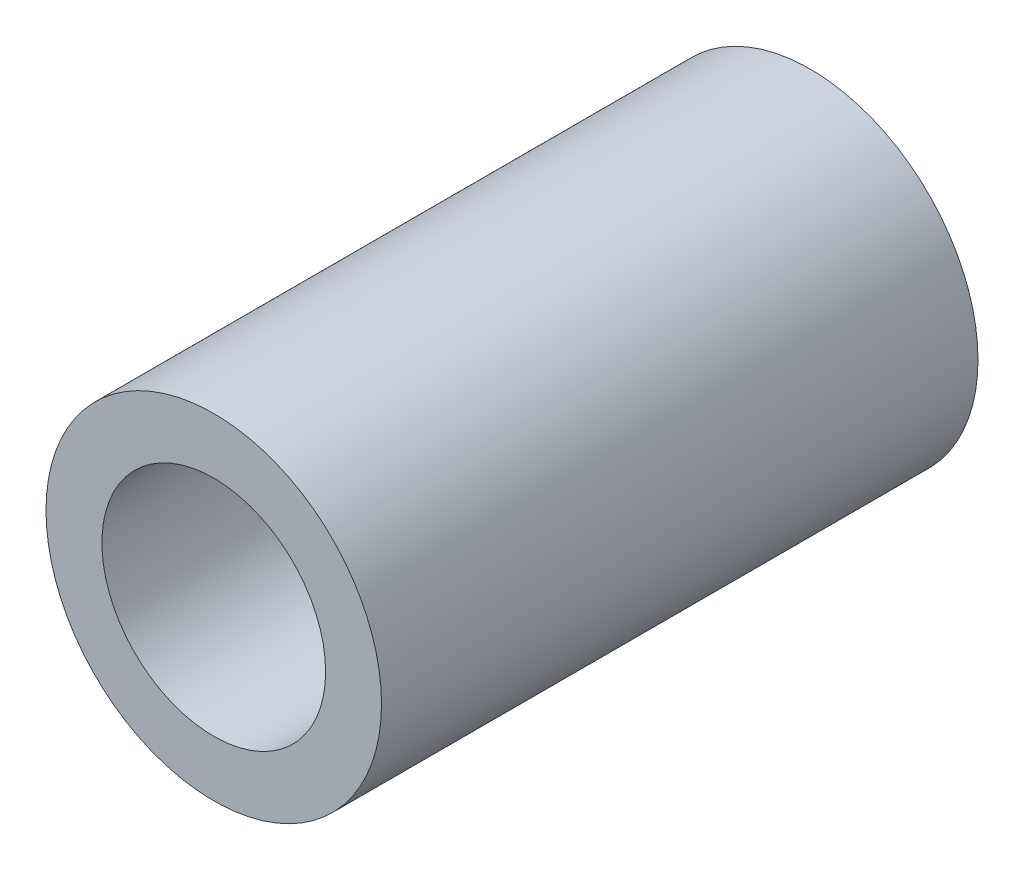
SolidWorks part; units mm, degrees
ref_plane "Płaszczyzna przednia" through (0, 0, 0) normal (0, 0, 1) x (1, 0, 0)
ref_plane "Płaszczyzna górna" through (0, 0, 0) normal (0, 1, 0) x (1, 0, 0)
ref_plane "Płaszczyzna prawa" through (0, 0, 0) normal (1, 0, 0) x (0, 0, -1)
sketch "Sketch1" plane through (0, 0, 0) normal (0, 0, 1) x (1, 0, 0)
  circle A0 centre (0, 0) radius 6
  circle A1 centre (0, 0) radius 9
  dimension "D1" = 3
  dimension "D2" = 12
extrude "Boss-Extrude1" add sketch "Sketch1" along normal mid plane 32
